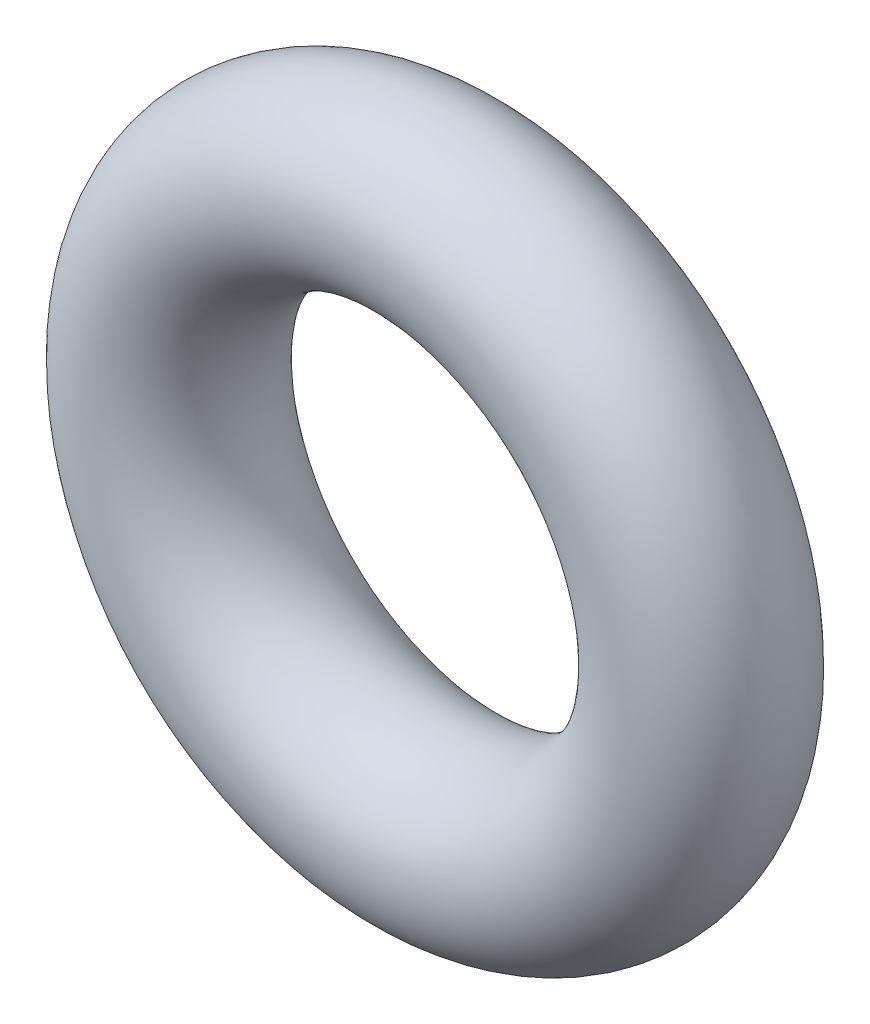
SolidWorks part; units mm, degrees
material "NBR"
ref_plane "Front" through (0, 0, 0) normal (0, 0, 1) x (1, 0, 0)
ref_plane "Top" through (0, 0, 0) normal (0, 1, 0) x (1, 0, 0)
ref_plane "Right" through (0, 0, 0) normal (1, 0, 0) x (0, 0, -1)
sketch "Sketch1" plane through (0, 0, 0) normal (1, 0, 0) x (0, -1, 0)
  line L0 (0, -0.889) -> (0, 0.889) construction
  line L2 (-3.9814, 0) -> (3.9814, 0) construction
  line L3 (-1.8415, 0) -> (1.8415, 0) construction
  circle A0 centre (2.7305, 0) radius 0.889
  point P9 (1.8415, 0)
  point P10 (3.6195, 0)
  point P13 (2.7305, 0.889)
  point P14 (2.7305, -0.889)
  dimension "Width" = 1.778
  dimension "ID" = 3.683
revolve "Revolve1" add sketch "Sketch1" angle 360 about L0
